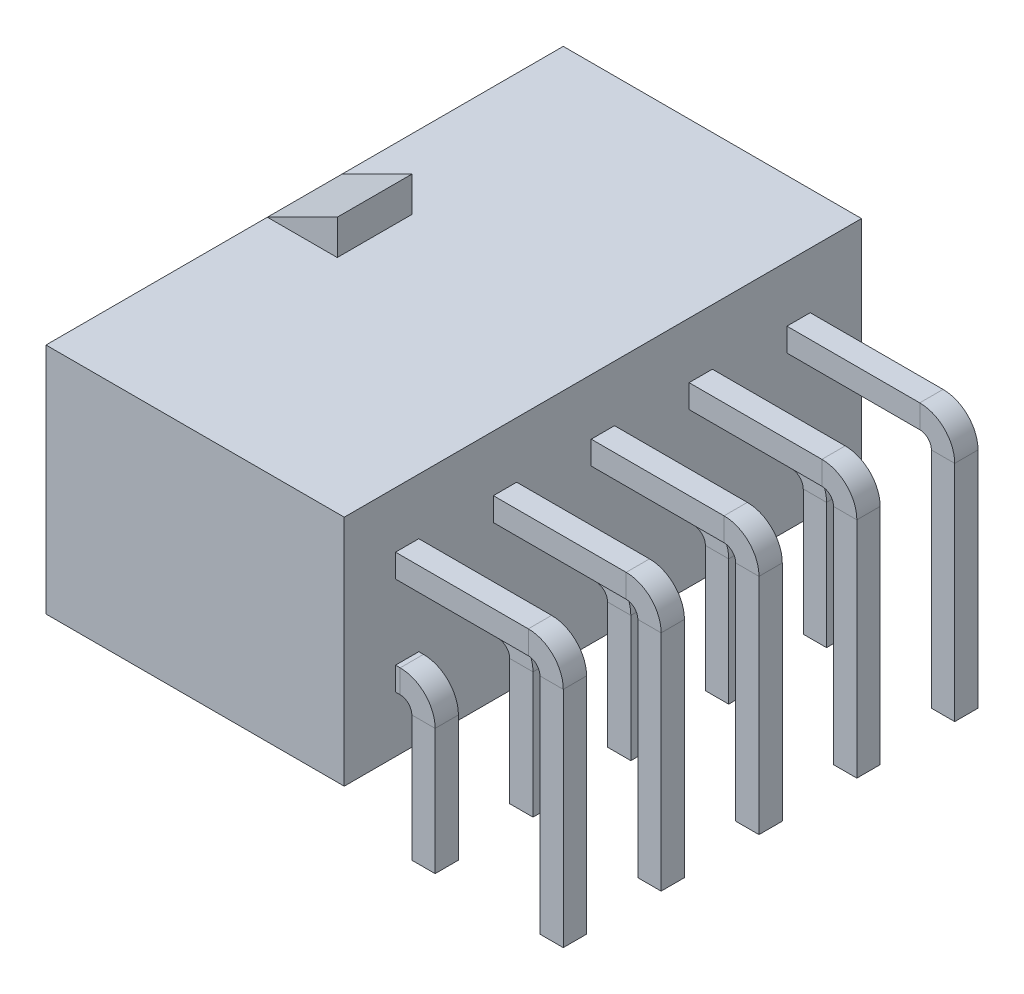
SolidWorks part; units mm, degrees
ref_plane "Спереди" through (0, 0, 0) normal (0, 0, 1) x (1, 0, 0)
ref_plane "Сверху" through (0, 0, 0) normal (0, 1, 0) x (1, 0, 0)
ref_plane "Справа" through (0, 0, 0) normal (1, 0, 0) x (0, 0, -1)
sketch "Эскиз1" plane through (0, 0, 0) normal (0, 1, 0) x (1, 0, 0)
  line L1 (-6.4, 11.1) -> (6.4, 11.1)
  line L2 (-6.4, 11.1) -> (-6.4, -11.1)
  line L3 (-6.4, -11.1) -> (6.4, -11.1)
  line L4 (6.4, 11.1) -> (6.4, -11.1)
extrude "Бобышка-Вытянуть1" add sketch "Эскиз1" along normal blind 10
sketch "Эскиз3" plane through (-6.4, 0, 0) normal (-1, 0, 0) x (0, 0, 1)
  line L14 (-10.4, 9.1) -> (-6.4, 9.1)
  line L15 (-10.4, 9.1) -> (-10.4, 5.1)
  line L16 (-10.4, 5.1) -> (-6.4, 5.1)
  line L17 (-6.4, 9.1) -> (-6.4, 5.1)
extrude "Вырез-Вытянуть1" cut sketch "Эскиз3" against normal blind 6.4
pattern_linear "Линейный массив1" count 5 spacing 4.2 along (0, 0, 1) count 2 spacing 4.2 along (0, -1, 0) of "Вырез-Вытянуть1"
ref_plane "Плоскость1" through (0, 0, 8.4) normal (0, 0, 1) x (1, 0, 0)
sketch "Эскиз12" plane through (6.4, 0, 0) normal (1, 0, 0) x (0, 0, -1)
  line L2 (-7.9, 7.6) -> (-8.9, 7.6)
  line L3 (-7.9, 7.6) -> (-7.9, 6.6)
  line L4 (-7.9, 6.6) -> (-8.9, 6.6)
  line L5 (-8.9, 7.6) -> (-8.9, 6.6)
  line L6 (-7.9, 7.6) -> (-8.9, 6.6) construction
  line L7 (-7.9, 6.6) -> (-8.9, 7.6) construction
  point P4 (-8.4, 7.1)
extrude "Вырез-Вытянуть2" cut sketch "Эскиз12" against normal up to surface (6.4 mm away) up to face at (0, 7.1, 8.4)
pattern_linear "Линейный массив2" count 5 spacing 4.2 along (0, 0, -1) count 2 spacing 4.2 along (0, -1, 0) of "Вырез-Вытянуть2"
ref_plane "Плоскость3" through (0, -3.5, 0) normal (0, 1, 0) x (1, 0, 0)
sketch "Эскиз14" plane through (0, -3.5, 0) normal (0, 1, 0) x (1, 0, 0)
  line L1 (12.6, -8.9) -> (13.6, -8.9)
  line L2 (12.6, -8.9) -> (12.6, -7.9)
  line L3 (12.6, -7.9) -> (13.6, -7.9)
  line L4 (13.6, -8.9) -> (13.6, -7.9)
  line L5 (12.6, -8.9) -> (13.6, -7.9) construction
  line L6 (12.6, -7.9) -> (13.6, -8.9) construction
  point P0 (13.1, -8.4)
sketch "Эскиз15" plane through (0, 0, 11.1) normal (0, 0, 1) x (1, 0, 0)
  line L0 (12.1, 7.1) -> (-3, 7.1)
  line L2 (13.1, 6.1) -> (13.1, -3.5)
  arc A0 (12.1, 7.1) -> (13.1, 6.1) centre (12.1, 6.1) cw
sweep "По траектории6" add profiles "Эскиз14" path "Эскиз15"
sketch "Эскиз16" plane through (0, -3.5, 0) normal (0, 1, 0) x (1, 0, 0)
  line L1 (7.1, -8.9) -> (8.1, -8.9)
  line L2 (7.1, -8.9) -> (7.1, -7.9)
  line L3 (7.1, -7.9) -> (8.1, -7.9)
  line L4 (8.1, -8.9) -> (8.1, -7.9)
  line L5 (7.1, -8.9) -> (8.1, -7.9) construction
  line L6 (7.1, -7.9) -> (8.1, -8.9) construction
  point P0 (7.6, -8.4)
sketch "Эскиз17" plane through (0, 0, 11.1) normal (0, 0, 1) x (1, 0, 0)
  line L0 (7.6, 1.9) -> (7.6, -3.5)
  line L1 (6.6, 2.9) -> (-3, 2.9)
  arc A0 (6.6, 2.9) -> (7.6, 1.9) centre (6.6, 1.9) cw
sweep "По траектории7" add profiles "Эскиз16" path "Эскиз17"
pattern_linear "Линейный массив3" count 5 spacing 4.2 along (0, 0, -1) of "По траектории6", "По траектории7"
sketch "Эскиз18" plane through (0, 10, 0) normal (0, 1, 0) x (1, 0, 0)
  line L1 (-3.4, 1.6) -> (-6.4, 1.6)
  line L2 (-3.4, 1.6) -> (-3.4, -1.6)
  line L3 (-3.4, -1.6) -> (-6.4, -1.6)
  line L4 (-6.4, 1.6) -> (-6.4, -1.6)
  line L5 (-3.4, 1.6) -> (-6.4, -1.6) construction
  line L6 (-3.4, -1.6) -> (-6.4, 1.6) construction
  point P0 (-4.9, 0)
extrude "Бобышка-Вытянуть2" add sketch "Эскиз18" along normal blind 1.5
sketch "Эскиз19" plane through (0, 0, 1.6) normal (0, 0, 1) x (1, 0, 0)
  line L0 (-3.4, 11.5) -> (-6.4, 10)
  line L1 (-6.4, 11.5) -> (-3.4, 11.5)
  line L2 (-6.4, 11.5) -> (-6.4, 10)
extrude "Вырез-Вытянуть3" cut sketch "Эскиз19" against normal up to surface (3.2 mm away) up to face at (-4.525, 10.9375, -1.6)
